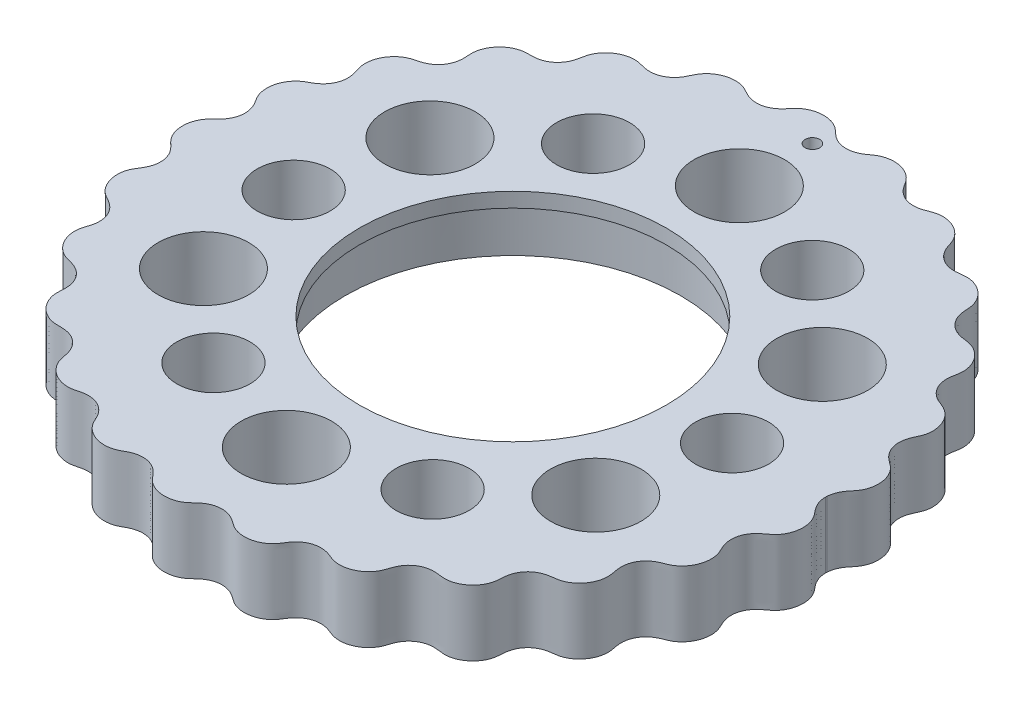
SolidWorks part; units mm, degrees
material "Like ABS"
ref_plane "Front Plane" through (0, 0, 0) normal (0, 0, 1) x (1, 0, 0)
ref_plane "Top Plane" through (0, 0, 0) normal (0, 1, 0) x (1, 0, 0)
ref_plane "Right Plane" through (0, 0, 0) normal (1, 0, 0) x (0, 0, -1)
sketch "Sketch1" plane through (0, 0, 0) normal (0, 1, 0) x (1, 0, 0)
  spline S0 degree 4 poles (18.6418, 10.5579) (18.7303, 10.3073) (18.9166, 10.0009) (19.2494, 9.7061) (19.7196, 9.4909) (20.0347, 9.3822) (20.3607, 9.2005) (20.6669, 8.9259) (20.9237, 8.5637) (21.1025, 8.1229) (21.1716, 7.6934) (21.1505, 7.3003) (21.0688, 6.9931) (20.9708, 6.7724) (20.8656, 6.5558) (20.7571, 6.3016) (20.668, 5.9591) (20.6615, 5.5306) (20.7798, 5.0848) (20.995, 4.7201) (21.2612, 4.4411) (21.5433, 4.2347) (21.8022, 4.0525) (22.045, 3.7986) (22.2501, 3.4744) (22.3932, 3.088) (22.4554, 2.6541) (22.4292, 2.264) (22.3433, 1.9326) (22.2197, 1.6594) (22.0797, 1.4428) (21.916, 1.2513) (21.7597, 1.0607) (21.6432, 0.8829) (21.5614, 0.7256) (21.5052, 0.5887) (21.4677, 0.4773) (21.4407, 0.371) (21.4222, 0.2789) (21.4076, 0.1762) (21.3996, 0.0464) (21.3987, -0.0271) (21.4069, -0.1732) (21.4219, -0.2777) (21.4443, -0.389) (21.474, -0.4968) (21.5197, -0.6294) (21.5968, -0.8019) (21.7184, -1.008) (21.898, -1.2319) (22.1006, -1.4645) (22.2832, -1.769) (22.4134, -2.1479) (22.4617, -2.5888) (22.4015, -3.0697) (22.2467, -3.4857) (22.0281, -3.8227) (21.7701, -4.0798) (21.5014, -4.2617) (21.2219, -4.4765) (20.9658, -4.7612) (20.7673, -5.1214) (20.6622, -5.5479) (20.6698, -5.9517) (20.758, -6.3091) (20.8905, -6.614) (21.0265, -6.8799) (21.1366, -7.2172) (21.1778, -7.6258) (21.1184, -8.0782) (20.9356, -8.544) (20.6762, -8.9143) (20.3782, -9.1865) (20.0975, -9.3492) (19.8699, -9.4384) (19.6428, -9.5272) (19.3961, -9.6431) (19.1116, -9.8349) (18.832, -10.1379) (18.628, -10.5267) (18.5387, -10.9199) (18.5379, -11.2864) (18.592, -11.6131) (18.6566, -11.9035) (18.677, -12.2563) (18.6137, -12.6603) (18.4454, -13.0751) (18.1627, -13.4684) (17.8328, -13.7578) (17.5261, -13.9295) (17.2611, -14.0207) (17.0556, -14.0631) (16.8894, -14.0847) (16.6814, -14.109) (16.4045, -14.1586) (16.0694, -14.2753) (15.709, -14.5087) (15.4048, -14.8538) (15.22, -15.2365) (15.1451, -15.5766) (15.1235, -15.8472) (15.1117, -16.0828) (15.086, -16.318) (15.0048, -16.6177) (14.8327, -16.9608) (14.5728, -17.2882) (14.2228, -17.573) (13.8443, -17.7633) (13.4619, -17.8627) (13.1375, -17.8769) (12.8864, -17.8466) (12.6365, -17.8129) (12.3547, -17.7936) (11.9999, -17.826) (11.5933, -17.9665) (11.2155, -18.2286) (10.9449, -18.555) (10.7906, -18.8655) (10.7038, -19.1216) (10.6339, -19.346) (10.5494, -19.5661) (10.3954, -19.8343) (10.1432, -20.1216) (9.8068, -20.3748) (9.389, -20.5646) (8.9692, -20.6515) (8.5724, -20.6465) (8.2199, -20.567) (7.923, -20.4379) (7.5842, -20.3142) (7.1893, -20.2495) (6.7562, -20.2849) (6.3193, -20.4504) (5.9761, -20.7038) (5.7522, -20.9667) (5.6061, -21.1928) (5.4827, -21.3919) (5.3455, -21.5826) (5.1293, -21.8019) (4.8139, -22.0153) (4.4253, -22.1753) (3.9731, -22.254) (3.5443, -22.2322) (3.1598, -22.1268) (2.8746, -21.9781) (2.6779, -21.8341) (2.4816, -21.6903) (2.2448, -21.5396) (1.9136, -21.3968) (1.4802, -21.3269) (1.0089, -21.3849) (0.6139, -21.5536) (0.3043, -21.7789) (0.0638, -22.0167) (-0.1578, -22.2142) (-0.448, -22.3889) (-0.804, -22.5195) (-1.2236, -22.5798) (-1.6888, -22.543) (-2.103, -22.4123) (-2.4495, -22.2124) (-2.7192, -21.9674) (-2.917, -21.7081) (-3.1594, -21.4371) (-3.4804, -21.1931) (-3.8955, -21.0162) (-4.3266, -20.9688) (-4.6986, -21.0199) (-5.0064, -21.124) (-5.2473, -21.2408) (-5.4821, -21.381) (-5.7377, -21.4982) (-6.0485, -21.5812) (-6.4098, -21.6099) (-6.8181, -21.5611) (-7.2514, -21.4098) (-7.6166, -21.1808) (-7.9026, -20.8985) (-8.1015, -20.5918) (-8.2285, -20.29) (-8.3985, -19.9669) (-8.652, -19.6514) (-9.0131, -19.3798) (-9.4202, -19.2304) (-9.7928, -19.1908) (-10.1152, -19.2172) (-10.3762, -19.2717) (-10.6376, -19.3487) (-10.9137, -19.3967) (-11.2341, -19.3981) (-11.5896, -19.3347) (-11.9717, -19.185) (-12.3532, -18.9296) (-12.6493, -18.6154) (-12.8557, -18.2686) (-12.9701, -17.92) (-13.0178, -17.5947) (-13.1323, -17.1226) (-13.3987, -16.6511) (-13.8075, -16.3174) (-14.2713, -16.1489) (-14.5895, -16.0966) (-14.8545, -16.0861) (-15.1259, -16.0953) (-15.4042, -16.0714) (-15.7134, -15.9919) (-16.04, -15.8412) (-16.3715, -15.6006) (-16.6766, -15.2574) (-16.8844, -14.8781) (-16.9969, -14.4887) (-17.0187, -14.1212) (-16.9833, -13.793) (-16.9797, -13.3053) (-17.125, -12.7827) (-17.4421, -12.3604) (-17.8514, -12.0856) (-18.1462, -11.9584) (-18.3995, -11.8839) (-18.6637, -11.8253) (-18.9258, -11.7315) (-19.2037, -11.5768) (-19.4806, -11.3493) (-19.7404, -11.0335) (-19.9495, -10.6246) (-20.0552, -10.2044) (-20.0656, -9.7977) (-19.9928, -9.4353) (-19.8758, -9.1255) (-19.784, -8.7675) (-19.7615, -8.359) (-19.8515, -7.9142) (-20.0565, -7.5324) (-20.3067, -7.2568) (-20.5604, -7.063) (-20.7872, -6.9295) (-21.0274, -6.8071) (-21.2562, -6.6501) (-21.4849, -6.4308) (-21.6945, -6.1418) (-21.8663, -5.7714) (-21.9656, -5.3231) (-21.9623, -4.8888) (-21.8783, -4.5321) (-21.7613, -4.2706) (-21.6335, -4.0565) (-21.4949, -3.8496) (-21.3375, -3.5602) (-21.217, -3.1677) (-21.1974, -2.7137) (-21.3049, -2.294) (-21.4811, -1.967) (-21.6794, -1.7187) (-21.866, -1.5347) (-22.0671, -1.3567) (-22.2478, -1.1472) (-22.4129, -0.878) (-22.5421, -0.5466) (-22.6173, -0.1335) (-22.5959, 0.3506) (-22.4661, 0.7918) (-22.2676, 1.1298) (-22.0677, 1.351) (-21.9165, 1.4911) (-21.796, 1.6037) (-21.6524, 1.752) (-21.4809, 1.9683) (-21.3145, 2.273) (-21.2055, 2.6829) (-21.2106, 3.1412) (-21.3262, 3.5408) (-21.5033, 3.8665) (-21.6848, 4.132) (-21.8148, 4.3747) (-21.9183, 4.6798) (-21.9709, 5.0457) (-21.9452, 5.4724) (-21.8071, 5.9373) (-21.6001, 6.2936) (-21.3746, 6.5445) (-21.1778, 6.703) (-21.036, 6.7965) (-20.8505, 6.8989) (-20.6264, 7.0191) (-20.3573, 7.2062) (-20.0813, 7.4975) (-19.8657, 7.8826) (-19.7711, 8.2901) (-19.7742, 8.6526) (-19.8318, 8.9622) (-19.9084, 9.2105) (-19.997, 9.4621) (-20.0507, 9.7317) (-20.0625, 10.045) (-20.0135, 10.3947) (-19.8723, 10.8081) (-19.6342, 11.1845) (-19.3432, 11.4777) (-19.047, 11.6699) (-18.8186, 11.7726) (-18.6046, 11.837) (-18.4132, 11.8827) (-18.176, 11.9484) (-17.9009, 12.0583) (-17.5928, 12.2516) (-17.2948, 12.562) (-17.0941, 12.9283) (-16.9937, 13.3178) (-16.9784, 13.6461) (-16.9965, 13.9004) (-17.0099, 14.1124) (-17.0076, 14.2827) (-16.9801, 14.5346) (-16.8899, 14.8605) (-16.7006, 15.227) (-16.3828, 15.5933) (-16.0373, 15.8442) (-15.7016, 15.9965) (-15.3896, 16.0736) (-15.1158, 16.0951) (-14.853, 16.0862) (-14.6003, 16.0964) (-14.3036, 16.1425) (-13.974, 16.253) (-13.6275, 16.4656) (-13.3337, 16.7849) (-13.1429, 17.1373) (-13.0488, 17.4509) (-13.004, 17.701) (-12.9637, 17.9088) (-12.9184, 18.0723) (-12.8283, 18.3082) (-12.6592, 18.5997) (-12.3841, 18.9062) (-11.9844, 19.1809) (-11.5862, 19.337) (-11.2216, 19.3996) (-10.8991, 19.395) (-10.6279, 19.3458) (-10.3747, 19.2715) (-10.1261, 19.2197) (-9.8257, 19.1924) (-9.4819, 19.2201) (-9.1008, 19.3403) (-8.7453, 19.5715) (-8.5077, 19.8241) (-8.3555, 20.0541) (-8.2592, 20.2364) (-8.1895, 20.3857) (-8.1029, 20.5726) (-7.9541, 20.8305) (-7.6939, 21.1232) (-7.3144, 21.3824) (-6.8604, 21.552) (-6.4441, 21.6079) (-6.0886, 21.5869) (-5.7814, 21.5126) (-5.5263, 21.405) (-5.2947, 21.2684) (-5.0616, 21.148) (-4.7636, 21.0366) (-4.3978, 20.9708) (-3.9655, 20.9994) (-3.5402, 21.1591) (-3.2052, 21.3959) (-2.9502, 21.6648) (-2.751, 21.9305) (-2.4845, 22.188) (-2.1352, 22.3988) (-1.7235, 22.5359) (-1.2663, 22.5795) (-0.8609, 22.5303) (-0.521, 22.4197) (-0.2417, 22.2695) (-0.0217, 22.0998) (0.1689, 21.9089) (0.3665, 21.7346) (0.6298, 21.5534) (0.9699, 21.4013) (1.3965, 21.3254) (1.8471, 21.3784) (2.228, 21.5266) (2.5394, 21.7249) (2.7977, 21.9316) (3.1198, 22.112) (3.5095, 22.2272) (3.9417, 22.2561) (4.3951, 22.1834) (4.7758, 22.0335) (5.0778, 21.8398) (5.3108, 21.6229) (5.4807, 21.402) (5.6181, 21.1687) (5.7678, 20.9505) (5.9804, 20.7099) (6.2746, 20.48) (6.6707, 20.304) (7.1201, 20.2475) (7.5241, 20.2991) (7.8729, 20.4154) (8.1735, 20.5505) (8.5298, 20.6425) (8.9343, 20.6554) (9.3591, 20.5746) (9.7795, 20.3902) (10.1108, 20.1489) (10.3549, 19.8842) (10.5259, 19.6143) (10.6343, 19.3565) (10.7093, 19.0953) (10.8019, 18.8462) (10.9504, 18.56) (11.1813, 18.2656) (11.5237, 17.9996) (11.9459, 17.8372) (12.3489, 17.79) (12.714, 17.818) (13.0377, 17.8733) (13.4043, 17.8713) (13.7973, 17.782) (14.1873, 17.5971) (14.5479, 17.3131) (14.8082, 16.9955) (14.9781, 16.6765) (15.0754, 16.3708) (15.1147, 16.0931) (15.1222, 15.8204) (15.1514, 15.5551) (15.2266, 15.2401) (15.3804, 14.8981) (15.6491, 14.5578) (16.0195, 14.2993) (16.3978, 14.1566) (16.7573, 14.0954) (17.0833, 14.0678) (17.4359, 13.9728) (17.7921, 13.7879) (18.1254, 13.5086) (18.4066, 13.1362) (18.5812, 12.7505) (18.6626, 12.3813) (18.6719, 12.0437) (18.6253, 11.7512) (18.553, 11.4218) (18.5268, 11.0409) (18.5933, 10.6174) (18.7938, 10.187) (19.0832, 9.8565) (19.4148, 9.6275) (19.7472, 9.4814) (20.0546, 9.3732) (20.3702, 9.1921) (20.6668, 8.9244) (20.9186, 8.5707) (21.0971, 8.1395) (21.1691, 7.7215) (21.1544, 7.3422) (21.0774, 7.012) (20.9574, 6.7402) (20.8057, 6.4375) (20.6875, 6.0727) (20.6502, 5.6447) (20.7419, 5.1786) (20.9432, 4.789) (21.2087, 4.4878) (21.4945, 4.2662) (21.7638, 4.0849) (22.0217, 3.8303) (22.2402, 3.4976) (22.393, 3.0964) (22.4576, 2.642) (22.4251, 2.2228) (22.319, 1.8567) (22.1767, 1.5831) (22.0373, 1.3938) (21.9111, 1.2447) (21.8119, 1.1238) (21.7086, 0.9838) (21.6226, 0.8451) (21.554, 0.7089) (21.5012, 0.5778) (21.4659, 0.4699) (21.4414, 0.3743) (21.425, 0.2922) (21.4143, 0.2199) (21.4075, 0.1593) (21.4009, 0.0789) (21.3996, 0.0181) (21.401, -0.0985) (21.4127, -0.2199) (21.4351, -0.355) (21.4779, -0.5212) (21.5509, -0.7067) (21.6442, -0.8848) (21.7553, -1.0512) (21.8797, -1.2084) (22.0099, -1.36) (22.1473, -1.5412) (22.273, -1.7627) (22.3996, -2.0988) (22.4619, -2.5279) (22.421, -3.0065) (22.26, -3.4597) (22.0444, -3.8016) (21.8211, -4.0307) (21.6332, -4.1724) (21.4416, -4.3083) (21.2215, -4.4808) (20.9709, -4.7472) (20.7583, -5.1317) (20.6554, -5.5913) (20.6785, -6.0142) (20.781, -6.3763) (20.9276, -6.6843) (21.0612, -6.963) (21.1479, -7.2947) (21.1712, -7.6682) (21.1116, -8.0834) (20.9479, -8.5165) (20.7051, -8.8812) (20.4074, -9.1649) (20.1242, -9.3365) (19.8924, -9.4302) (19.6596, -9.5199) (19.387, -9.6456) (19.0617, -9.8691) (18.834, -10.1425) (18.7105, -10.38) (18.6618, -10.5041) knots 0 0 0 0 0 0.005903 0.00775 0.009596 0.011443 0.013289 0.015968 0.018648 0.021201 0.023754 0.025536 0.027318 0.028209 0.0291 0.030883 0.033442 0.036001 0.038491 0.040982 0.042735 0.044487 0.04624 0.047993 0.05047 0.052947 0.055301 0.057654 0.059079 0.060504 0.061928 0.063353 0.064664 0.065974 0.066629 0.067284 0.067939 0.068594 0.069018 0.069442 0.07029 0.070911 0.071532 0.072154 0.072775 0.073396 0.074017 0.07526 0.076968 0.078675 0.080383 0.082091 0.084795 0.087498 0.090125 0.092752 0.094549 0.096347 0.098144 0.099942 0.102358 0.104774 0.107172 0.10957 0.111226 0.112881 0.114537 0.116192 0.119053 0.121914 0.124551 0.127187 0.128992 0.130797 0.1317 0.132602 0.134407 0.136832 0.139257 0.141646 0.144036 0.145684 0.147333 0.148982 0.15063 0.15348 0.156329 0.158805 0.161281 0.16314 0.164069 0.164999 0.165928 0.166858 0.168717 0.171229 0.173741 0.176268 0.178796 0.180542 0.181414 0.182287 0.184033 0.185778 0.188262 0.190745 0.19323 0.195716 0.197582 0.199449 0.200382 0.201316 0.203182 0.205703 0.208224 0.210741 0.213258 0.214997 0.215867 0.216736 0.218475 0.220214 0.222688 0.225161 0.22774 0.230318 0.232111 0.233904 0.235697 0.237491 0.240099 0.242708 0.245214 0.24772 0.249453 0.250319 0.251185 0.252918 0.25465 0.257114 0.259577 0.262166 0.264755 0.266555 0.268355 0.269255 0.270155 0.271956 0.274573 0.277191 0.279769 0.282346 0.283988 0.285631 0.287273 0.288916 0.291455 0.293994 0.296593 0.299192 0.300999 0.302806 0.304614 0.306421 0.309048 0.311675 0.314492 0.315901 0.317309 0.318863 0.320416 0.32197 0.323523 0.325967 0.32841 0.331019 0.333628 0.335442 0.337257 0.339071 0.340886 0.343522 0.346158 0.348962 0.350365 0.351767 0.353315 0.354863 0.356411 0.357959 0.360393 0.362826 0.365445 0.368064 0.369886 0.371707 0.373529 0.37535 0.380641 0.383432 0.384828 0.386224 0.387767 0.389309 0.390852 0.392395 0.394819 0.397243 0.399871 0.4025 0.404329 0.406157 0.407986 0.409814 0.415123 0.417902 0.419291 0.42068 0.422218 0.423755 0.425293 0.42683 0.429244 0.431659 0.434298 0.436936 0.438772 0.440607 0.442443 0.444278 0.446942 0.449606 0.452371 0.453754 0.455136 0.456668 0.458201 0.459733 0.461265 0.46367 0.466075 0.468724 0.471372 0.473215 0.474136 0.475057 0.476899 0.478742 0.481415 0.484087 0.486839 0.488215 0.489591 0.491119 0.492646 0.494173 0.4957 0.498096 0.500491 0.503422 0.506353 0.508183 0.509098 0.510013 0.510928 0.511843 0.513673 0.51612 0.518568 0.521142 0.523716 0.525237 0.526758 0.52828 0.529801 0.532354 0.534907 0.537685 0.540462 0.541402 0.542343 0.543283 0.544223 0.546104 0.547984 0.550517 0.553049 0.555775 0.557137 0.5585 0.560017 0.561535 0.563052 0.56457 0.566946 0.569323 0.572675 0.574351 0.576028 0.577119 0.578211 0.579302 0.580394 0.582577 0.58476 0.5873 0.589839 0.591724 0.593609 0.594552 0.595495 0.596437 0.59738 0.600165 0.60295 0.605495 0.608041 0.609559 0.611076 0.612594 0.614112 0.615394 0.616676 0.619241 0.621771 0.6243 0.626179 0.628058 0.628997 0.629937 0.630876 0.631815 0.63459 0.637365 0.639921 0.642477 0.643999 0.645522 0.647045 0.648567 0.649856 0.651144 0.653721 0.656167 0.658613 0.660441 0.661355 0.662269 0.663183 0.664097 0.665925 0.668853 0.671781 0.674179 0.676577 0.678106 0.679634 0.681163 0.682691 0.684069 0.685447 0.688203 0.690873 0.693543 0.695384 0.697224 0.699065 0.700905 0.703551 0.706197 0.708605 0.711012 0.712546 0.714079 0.715613 0.717147 0.718531 0.719916 0.722685 0.725346 0.728007 0.72984 0.731674 0.733508 0.735341 0.737977 0.740613 0.74303 0.745447 0.746986 0.748525 0.750064 0.751603 0.752994 0.754385 0.757167 0.759819 0.762471 0.764297 0.766124 0.767951 0.769777 0.772403 0.77503 0.777456 0.779883 0.781427 0.782971 0.784515 0.786059 0.787457 0.788854 0.79165 0.794292 0.796935 0.798755 0.800574 0.802394 0.804213 0.80683 0.809446 0.811882 0.814318 0.815868 0.817417 0.818967 0.820516 0.82192 0.823324 0.826132 0.828766 0.8314 0.833212 0.835025 0.836837 0.83865 0.841256 0.843862 0.846393 0.848925 0.850563 0.852201 0.85384 0.855478 0.858047 0.860616 0.86324 0.865865 0.86767 0.869476 0.871281 0.873086 0.875682 0.878279 0.88082 0.883362 0.885006 0.88665 0.888295 0.889939 0.892519 0.8951 0.897715 0.90033 0.902128 0.903927 0.905725 0.907523 0.910109 0.912695 0.915161 0.917628 0.919362 0.921096 0.921963 0.92283 0.923698 0.924565 0.925819 0.926447 0.927074 0.927701 0.928329 0.928642 0.928956 0.929269 0.929583 0.930436 0.930863 0.93129 0.932399 0.933509 0.934619 0.935729 0.936839 0.937948 0.939058 0.940168 0.941873 0.943578 0.946988 0.949698 0.952408 0.954146 0.955884 0.956753 0.957622 0.95936 0.962081 0.964802 0.967235 0.969667 0.971378 0.973089 0.9748 0.976511 0.978929 0.981347 0.984027 0.986707 0.988553 0.990399 0.991323 0.992246 0.994092 0.997046 1 1 1 1 1 construction
  spline S1 degree 4 poles (21.4, 0) (21.4, -0.0241) (21.4013, -0.0728) (21.4069, -0.1732) (21.4219, -0.2777) (21.4443, -0.389) (21.474, -0.4968) (21.5197, -0.6294) (21.5968, -0.8019) (21.7184, -1.008) (21.898, -1.2319) (22.1006, -1.4645) (22.2832, -1.769) (22.4134, -2.1479) (22.4617, -2.5888) (22.4015, -3.0697) (22.2467, -3.4857) (22.0281, -3.8227) (21.7701, -4.0798) (21.5014, -4.2617) (21.2219, -4.4765) (20.9658, -4.7612) (20.7673, -5.1214) (20.6622, -5.5479) (20.6698, -5.9517) (20.758, -6.3091) (20.8905, -6.614) (21.0265, -6.8799) (21.1366, -7.2172) (21.1778, -7.6258) (21.1184, -8.0782) (20.9356, -8.544) (20.6762, -8.9143) (20.3782, -9.1865) (20.0975, -9.3492) (19.8699, -9.4384) (19.6428, -9.5272) (19.3961, -9.6431) (19.1116, -9.8349) (18.832, -10.1379) (18.628, -10.5267) (18.5387, -10.9199) (18.5379, -11.2864) (18.592, -11.6131) (18.6566, -11.9035) (18.677, -12.2563) (18.6137, -12.6603) (18.4454, -13.0751) (18.1627, -13.4684) (17.8328, -13.7578) (17.5261, -13.9295) (17.2611, -14.0207) (17.0556, -14.0631) (16.8894, -14.0847) (16.6814, -14.109) (16.4045, -14.1586) (16.0694, -14.2753) (15.709, -14.5087) (15.4048, -14.8538) (15.22, -15.2365) (15.1451, -15.5766) (15.1235, -15.8472) (15.1117, -16.0828) (15.086, -16.318) (15.0048, -16.6177) (14.8327, -16.9608) (14.5728, -17.2882) (14.2228, -17.573) (13.8443, -17.7633) (13.4619, -17.8627) (13.1375, -17.8769) (12.8864, -17.8466) (12.6365, -17.8129) (12.3547, -17.7936) (11.9999, -17.826) (11.5933, -17.9665) (11.2155, -18.2286) (10.9449, -18.555) (10.7906, -18.8655) (10.7038, -19.1216) (10.6339, -19.346) (10.5494, -19.5661) (10.3954, -19.8343) (10.1432, -20.1216) (9.8068, -20.3748) (9.389, -20.5646) (8.9692, -20.6515) (8.5724, -20.6465) (8.2199, -20.567) (7.923, -20.4379) (7.5842, -20.3142) (7.1893, -20.2495) (6.7562, -20.2849) (6.3193, -20.4504) (5.9761, -20.7038) (5.7522, -20.9667) (5.6061, -21.1928) (5.4827, -21.3919) (5.3455, -21.5826) (5.1293, -21.8019) (4.8139, -22.0153) (4.4253, -22.1753) (3.9731, -22.254) (3.5443, -22.2322) (3.1598, -22.1268) (2.8746, -21.9781) (2.6779, -21.8341) (2.4816, -21.6903) (2.2448, -21.5396) (1.9136, -21.3968) (1.4802, -21.3269) (1.0089, -21.3849) (0.6139, -21.5536) (0.3043, -21.7789) (0.0638, -22.0167) (-0.1578, -22.2142) (-0.448, -22.3889) (-0.804, -22.5195) (-1.2236, -22.5798) (-1.6888, -22.543) (-2.103, -22.4123) (-2.4495, -22.2124) (-2.7192, -21.9674) (-2.917, -21.7081) (-3.1594, -21.4371) (-3.4804, -21.1931) (-3.8955, -21.0162) (-4.3266, -20.9688) (-4.6986, -21.0199) (-5.0064, -21.124) (-5.2473, -21.2408) (-5.4821, -21.381) (-5.7377, -21.4982) (-6.0485, -21.5812) (-6.4098, -21.6099) (-6.8181, -21.5611) (-7.2514, -21.4098) (-7.6166, -21.1808) (-7.9026, -20.8985) (-8.1015, -20.5918) (-8.2285, -20.29) (-8.3985, -19.9669) (-8.652, -19.6514) (-9.0131, -19.3798) (-9.4202, -19.2304) (-9.7928, -19.1908) (-10.1152, -19.2172) (-10.3762, -19.2717) (-10.6376, -19.3487) (-10.9137, -19.3967) (-11.2341, -19.3981) (-11.5896, -19.3347) (-11.9717, -19.185) (-12.3532, -18.9296) (-12.6493, -18.6154) (-12.8557, -18.2686) (-12.9701, -17.92) (-13.0178, -17.5947) (-13.1323, -17.1226) (-13.3987, -16.6511) (-13.8075, -16.3174) (-14.2713, -16.1489) (-14.5895, -16.0966) (-14.8545, -16.0861) (-15.1259, -16.0953) (-15.4042, -16.0714) (-15.7134, -15.9919) (-16.04, -15.8412) (-16.3715, -15.6006) (-16.6766, -15.2574) (-16.8844, -14.8781) (-16.9969, -14.4887) (-17.0187, -14.1212) (-16.9833, -13.793) (-16.9797, -13.3053) (-17.125, -12.7827) (-17.4421, -12.3604) (-17.8514, -12.0856) (-18.1462, -11.9584) (-18.3995, -11.8839) (-18.6637, -11.8253) (-18.9258, -11.7315) (-19.2037, -11.5768) (-19.4806, -11.3493) (-19.7404, -11.0335) (-19.9495, -10.6246) (-20.0552, -10.2044) (-20.0656, -9.7977) (-19.9928, -9.4353) (-19.8758, -9.1255) (-19.784, -8.7675) (-19.7615, -8.359) (-19.8515, -7.9142) (-20.0565, -7.5324) (-20.3067, -7.2568) (-20.5604, -7.063) (-20.7872, -6.9295) (-21.0274, -6.8071) (-21.2562, -6.6501) (-21.4849, -6.4308) (-21.6945, -6.1418) (-21.8663, -5.7714) (-21.9656, -5.3231) (-21.9623, -4.8888) (-21.8783, -4.5321) (-21.7613, -4.2706) (-21.6335, -4.0565) (-21.4949, -3.8496) (-21.3375, -3.5602) (-21.217, -3.1677) (-21.1974, -2.7137) (-21.3049, -2.294) (-21.4811, -1.967) (-21.6794, -1.7187) (-21.866, -1.5347) (-22.0671, -1.3567) (-22.2478, -1.1472) (-22.4129, -0.878) (-22.5421, -0.5466) (-22.6173, -0.1335) (-22.5959, 0.3506) (-22.4661, 0.7918) (-22.2676, 1.1298) (-22.0677, 1.351) (-21.9165, 1.4911) (-21.796, 1.6037) (-21.6524, 1.752) (-21.4809, 1.9683) (-21.3145, 2.273) (-21.2055, 2.6829) (-21.2106, 3.1412) (-21.3262, 3.5408) (-21.5033, 3.8665) (-21.6848, 4.132) (-21.8148, 4.3747) (-21.9183, 4.6798) (-21.9709, 5.0457) (-21.9452, 5.4724) (-21.8071, 5.9373) (-21.6001, 6.2936) (-21.3746, 6.5445) (-21.1778, 6.703) (-21.036, 6.7965) (-20.8505, 6.8989) (-20.6264, 7.0191) (-20.3573, 7.2062) (-20.0813, 7.4975) (-19.8657, 7.8826) (-19.7711, 8.2901) (-19.7742, 8.6526) (-19.8318, 8.9622) (-19.9084, 9.2105) (-19.997, 9.4621) (-20.0507, 9.7317) (-20.0625, 10.045) (-20.0135, 10.3947) (-19.8723, 10.8081) (-19.6342, 11.1845) (-19.3432, 11.4777) (-19.047, 11.6699) (-18.8186, 11.7726) (-18.6046, 11.837) (-18.4132, 11.8827) (-18.176, 11.9484) (-17.9009, 12.0583) (-17.5928, 12.2516) (-17.2948, 12.562) (-17.0941, 12.9283) (-16.9937, 13.3178) (-16.9784, 13.6461) (-16.9965, 13.9004) (-17.0099, 14.1124) (-17.0076, 14.2827) (-16.9801, 14.5346) (-16.8899, 14.8605) (-16.7006, 15.227) (-16.3828, 15.5933) (-16.0373, 15.8442) (-15.7016, 15.9965) (-15.3896, 16.0736) (-15.1158, 16.0951) (-14.853, 16.0862) (-14.6003, 16.0964) (-14.3036, 16.1425) (-13.974, 16.253) (-13.6275, 16.4656) (-13.3337, 16.7849) (-13.1429, 17.1373) (-13.0488, 17.4509) (-13.004, 17.701) (-12.9637, 17.9088) (-12.9184, 18.0723) (-12.8283, 18.3082) (-12.6592, 18.5997) (-12.3841, 18.9062) (-11.9844, 19.1809) (-11.5862, 19.337) (-11.2216, 19.3996) (-10.8991, 19.395) (-10.6279, 19.3458) (-10.3747, 19.2715) (-10.1261, 19.2197) (-9.8257, 19.1924) (-9.4819, 19.2201) (-9.1008, 19.3403) (-8.7453, 19.5715) (-8.5077, 19.8241) (-8.3555, 20.0541) (-8.2592, 20.2364) (-8.1895, 20.3857) (-8.1029, 20.5726) (-7.9541, 20.8305) (-7.6939, 21.1232) (-7.3144, 21.3824) (-6.8604, 21.552) (-6.4441, 21.6079) (-6.0886, 21.5869) (-5.7814, 21.5126) (-5.5263, 21.405) (-5.2947, 21.2684) (-5.0616, 21.148) (-4.7636, 21.0366) (-4.3978, 20.9708) (-3.9655, 20.9994) (-3.5402, 21.1591) (-3.2052, 21.3959) (-2.9502, 21.6648) (-2.751, 21.9305) (-2.4845, 22.188) (-2.1352, 22.3988) (-1.7235, 22.5359) (-1.2663, 22.5795) (-0.8609, 22.5303) (-0.521, 22.4197) (-0.2417, 22.2695) (-0.0217, 22.0998) (0.1689, 21.9089) (0.3665, 21.7346) (0.6298, 21.5534) (0.9699, 21.4013) (1.3965, 21.3254) (1.8471, 21.3784) (2.228, 21.5266) (2.5394, 21.7249) (2.7977, 21.9316) (3.1198, 22.112) (3.5095, 22.2272) (3.9417, 22.2561) (4.3951, 22.1834) (4.7758, 22.0335) (5.0778, 21.8398) (5.3108, 21.6229) (5.4807, 21.402) (5.6181, 21.1687) (5.7678, 20.9505) (5.9804, 20.7099) (6.2746, 20.48) (6.6707, 20.304) (7.1201, 20.2475) (7.5241, 20.2991) (7.8729, 20.4154) (8.1735, 20.5505) (8.5298, 20.6425) (8.9343, 20.6554) (9.3591, 20.5746) (9.7795, 20.3902) (10.1108, 20.1489) (10.3549, 19.8842) (10.5259, 19.6143) (10.6343, 19.3565) (10.7093, 19.0953) (10.8019, 18.8462) (10.9504, 18.56) (11.1813, 18.2656) (11.5237, 17.9996) (11.9459, 17.8372) (12.3489, 17.79) (12.714, 17.818) (13.0377, 17.8733) (13.4043, 17.8713) (13.7973, 17.782) (14.1873, 17.5971) (14.5479, 17.3131) (14.8082, 16.9955) (14.9781, 16.6765) (15.0754, 16.3708) (15.1147, 16.0931) (15.1222, 15.8204) (15.1514, 15.5551) (15.2266, 15.2401) (15.3804, 14.8981) (15.6491, 14.5578) (16.0195, 14.2993) (16.3978, 14.1566) (16.7573, 14.0954) (17.0833, 14.0678) (17.4359, 13.9728) (17.7921, 13.7879) (18.1254, 13.5086) (18.4066, 13.1362) (18.5812, 12.7505) (18.6626, 12.3813) (18.6719, 12.0437) (18.6253, 11.7512) (18.553, 11.4218) (18.5268, 11.0409) (18.5933, 10.6174) (18.7938, 10.187) (19.0832, 9.8565) (19.4148, 9.6275) (19.7472, 9.4814) (20.0546, 9.3732) (20.3702, 9.1921) (20.6668, 8.9244) (20.9186, 8.5707) (21.0971, 8.1395) (21.1691, 7.7215) (21.1544, 7.3422) (21.0774, 7.012) (20.9574, 6.7402) (20.8057, 6.4375) (20.6875, 6.0727) (20.6502, 5.6447) (20.7419, 5.1786) (20.9432, 4.789) (21.2087, 4.4878) (21.4945, 4.2662) (21.7638, 4.0849) (22.0217, 3.8303) (22.2402, 3.4976) (22.393, 3.0964) (22.4576, 2.642) (22.4251, 2.2228) (22.319, 1.8567) (22.1767, 1.5831) (22.0373, 1.3938) (21.9111, 1.2447) (21.8119, 1.1238) (21.7086, 0.9838) (21.6226, 0.8451) (21.554, 0.7089) (21.5012, 0.5778) (21.4659, 0.4699) (21.4414, 0.3743) (21.425, 0.2922) (21.4143, 0.2199) (21.4075, 0.1593) (21.404, 0.1171) (21.4025, 0.0924) (21.4019, 0.0803) knots 0.07029 0.07029 0.07029 0.07029 0.07029 0.070911 0.071532 0.072154 0.072775 0.073396 0.074017 0.07526 0.076968 0.078675 0.080383 0.082091 0.084795 0.087498 0.090125 0.092752 0.094549 0.096347 0.098144 0.099942 0.102358 0.104774 0.107172 0.10957 0.111226 0.112881 0.114537 0.116192 0.119053 0.121914 0.124551 0.127187 0.128992 0.130797 0.1317 0.132602 0.134407 0.136832 0.139257 0.141646 0.144036 0.145684 0.147333 0.148982 0.15063 0.15348 0.156329 0.158805 0.161281 0.16314 0.164069 0.164999 0.165928 0.166858 0.168717 0.171229 0.173741 0.176268 0.178796 0.180542 0.181414 0.182287 0.184033 0.185778 0.188262 0.190745 0.19323 0.195716 0.197582 0.199449 0.200382 0.201316 0.203182 0.205703 0.208224 0.210741 0.213258 0.214997 0.215867 0.216736 0.218475 0.220214 0.222688 0.225161 0.22774 0.230318 0.232111 0.233904 0.235697 0.237491 0.240099 0.242708 0.245214 0.24772 0.249453 0.250319 0.251185 0.252918 0.25465 0.257114 0.259577 0.262166 0.264755 0.266555 0.268355 0.269255 0.270155 0.271956 0.274573 0.277191 0.279769 0.282346 0.283988 0.285631 0.287273 0.288916 0.291455 0.293994 0.296593 0.299192 0.300999 0.302806 0.304614 0.306421 0.309048 0.311675 0.314492 0.315901 0.317309 0.318863 0.320416 0.32197 0.323523 0.325967 0.32841 0.331019 0.333628 0.335442 0.337257 0.339071 0.340886 0.343522 0.346158 0.348962 0.350365 0.351767 0.353315 0.354863 0.356411 0.357959 0.360393 0.362826 0.365445 0.368064 0.369886 0.371707 0.373529 0.37535 0.380641 0.383432 0.384828 0.386224 0.387767 0.389309 0.390852 0.392395 0.394819 0.397243 0.399871 0.4025 0.404329 0.406157 0.407986 0.409814 0.415123 0.417902 0.419291 0.42068 0.422218 0.423755 0.425293 0.42683 0.429244 0.431659 0.434298 0.436936 0.438772 0.440607 0.442443 0.444278 0.446942 0.449606 0.452371 0.453754 0.455136 0.456668 0.458201 0.459733 0.461265 0.46367 0.466075 0.468724 0.471372 0.473215 0.474136 0.475057 0.476899 0.478742 0.481415 0.484087 0.486839 0.488215 0.489591 0.491119 0.492646 0.494173 0.4957 0.498096 0.500491 0.503422 0.506353 0.508183 0.509098 0.510013 0.510928 0.511843 0.513673 0.51612 0.518568 0.521142 0.523716 0.525237 0.526758 0.52828 0.529801 0.532354 0.534907 0.537685 0.540462 0.541402 0.542343 0.543283 0.544223 0.546104 0.547984 0.550517 0.553049 0.555775 0.557137 0.5585 0.560017 0.561535 0.563052 0.56457 0.566946 0.569323 0.572675 0.574351 0.576028 0.577119 0.578211 0.579302 0.580394 0.582577 0.58476 0.5873 0.589839 0.591724 0.593609 0.594552 0.595495 0.596437 0.59738 0.600165 0.60295 0.605495 0.608041 0.609559 0.611076 0.612594 0.614112 0.615394 0.616676 0.619241 0.621771 0.6243 0.626179 0.628058 0.628997 0.629937 0.630876 0.631815 0.63459 0.637365 0.639921 0.642477 0.643999 0.645522 0.647045 0.648567 0.649856 0.651144 0.653721 0.656167 0.658613 0.660441 0.661355 0.662269 0.663183 0.664097 0.665925 0.668853 0.671781 0.674179 0.676577 0.678106 0.679634 0.681163 0.682691 0.684069 0.685447 0.688203 0.690873 0.693543 0.695384 0.697224 0.699065 0.700905 0.703551 0.706197 0.708605 0.711012 0.712546 0.714079 0.715613 0.717147 0.718531 0.719916 0.722685 0.725346 0.728007 0.72984 0.731674 0.733508 0.735341 0.737977 0.740613 0.74303 0.745447 0.746986 0.748525 0.750064 0.751603 0.752994 0.754385 0.757167 0.759819 0.762471 0.764297 0.766124 0.767951 0.769777 0.772403 0.77503 0.777456 0.779883 0.781427 0.782971 0.784515 0.786059 0.787457 0.788854 0.79165 0.794292 0.796935 0.798755 0.800574 0.802394 0.804213 0.80683 0.809446 0.811882 0.814318 0.815868 0.817417 0.818967 0.820516 0.82192 0.823324 0.826132 0.828766 0.8314 0.833212 0.835025 0.836837 0.83865 0.841256 0.843862 0.846393 0.848925 0.850563 0.852201 0.85384 0.855478 0.858047 0.860616 0.86324 0.865865 0.86767 0.869476 0.871281 0.873086 0.875682 0.878279 0.88082 0.883362 0.885006 0.88665 0.888295 0.889939 0.892519 0.8951 0.897715 0.90033 0.902128 0.903927 0.905725 0.907523 0.910109 0.912695 0.915161 0.917628 0.919362 0.921096 0.921963 0.92283 0.923698 0.924565 0.925819 0.926447 0.927074 0.927701 0.928329 0.928642 0.928956 0.929269 0.929583 0.929583 0.929583 0.929583 0.929583
  spline S2 degree 1 poles (21.4019, 0.0803) (21.4, 0) knots 0 0 1 1
extrude "Boss-Extrude1" add sketch "Sketch1" along normal blind 4.5
sketch "Sketch2" plane through (0, 4.5, 0) normal (0, 1, 0) x (1, 0, 0)
  circle A0 centre (0, 0) radius 11.475
  dimension "D1" = 22.95
extrude "Cut-Extrude1" cut sketch "Sketch2" against normal up to surface (4.5 mm away) up to face at (21.401, 0, -0.0402)
sketch "Sketch3" plane through (0, 4.5, 0) normal (0, 1, 0) x (1, 0, 0)
  line L0 (0, 0) -> (0, 15.5) construction
  circle A0 centre (0, 15.5) radius 3.1
  dimension "D1" = 6.2
  dimension "D2" = 15.5
extrude "Cut-Extrude2" cut sketch "Sketch3" against normal up to surface (4.5 mm away) up to face at (0, 0, -11.475)
pattern_circular "CirPattern1" count 6 over 360 about axis through (0, 0, 0) along (0, 1, 0) of "Cut-Extrude2"
sketch "Sketch5" plane through (0, 4.5, 0) normal (0, 1, 0) x (1, 0, 0)
  line L0 (0, 15.5) -> (0, 0) construction
  line L1 (0, 0) -> (-7.5, 12.9904) construction
  circle A0 centre (-7.5, 12.9904) radius 2.5
  dimension "D2" = 5
  dimension "D1" = 30
  dimension "D3" = 15
extrude "Cut-Extrude3" cut sketch "Sketch5" against normal up to surface (4.5 mm away) up to face at (-13.4234, 0, -10.85)
pattern_circular "CirPattern2" count 6 over 360 about axis through (0, 0, 0) along (0, 1, 0) of "Cut-Extrude3"
sketch "Sketch6" plane through (0, 4.5, 0) normal (0, 1, 0) x (1, 0, 0)
  circle A0 centre (0, 0) radius 11.7376
  circle A1 centre (0, 0) radius 10.5
  dimension "D1" = 21
extrude "Boss-Extrude2" add sketch "Sketch6" against normal blind 1
sketch "Sketch7" plane through (0, 4.5, 0) normal (0, 1, 0) x (1, 0, 0)
  line L2 (0, 0) -> (0, 20.5) construction
  circle A1 centre (0, 20.5) radius 0.5
  dimension "D4" = 1
  dimension "D3" = 20.5
extrude "Cut-Extrude4" cut sketch "Sketch7" against normal up to surface (4.5 mm away) up to face at (-15, 0, -2.5)
